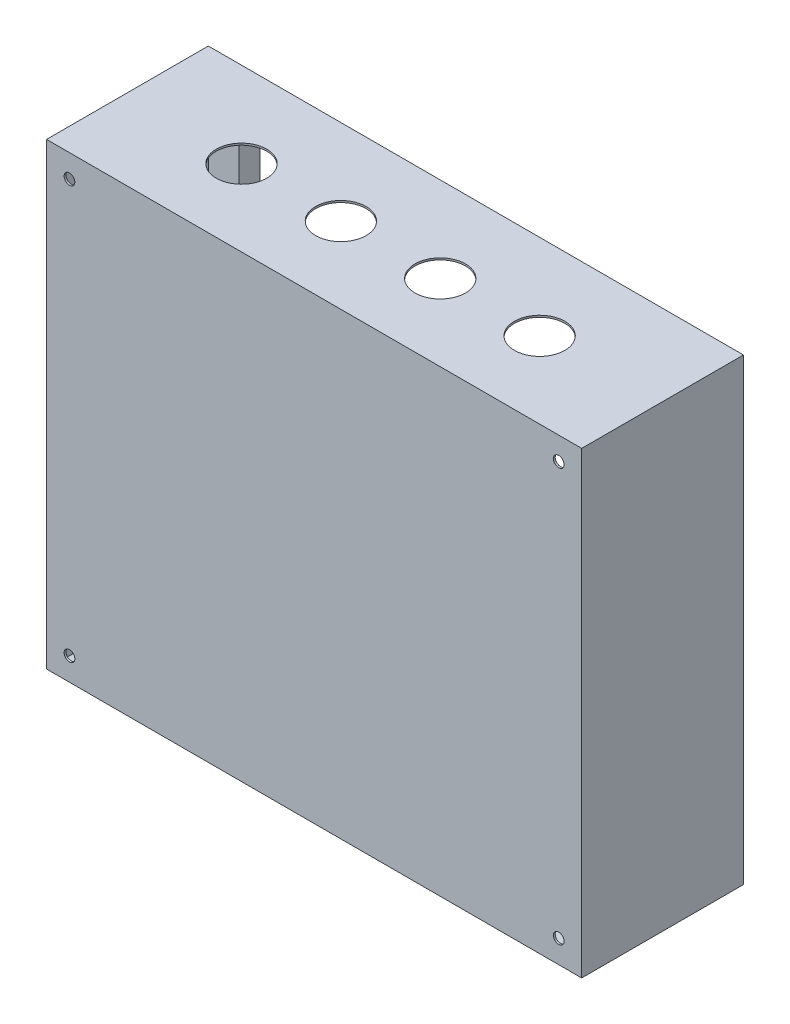
SolidWorks part; units mm, degrees
ref_plane "前视基准面" through (0, 0, 0) normal (0, 0, 1) x (1, 0, 0)
ref_plane "上视基准面" through (0, 0, 0) normal (0, 1, 0) x (1, 0, 0)
ref_plane "右视基准面" through (0, 0, 0) normal (1, 0, 0) x (0, 0, -1)
sketch "草图1" plane through (0, 0, 0) normal (0, 0, 1) x (1, 0, 0)
  line L0 (-175, -150) -> (-175, 150)
  line L1 (-175, -150) -> (175, -150)
  line L2 (-175, 150) -> (175, 150)
  line L3 (175, -150) -> (175, 150)
  line L4 (-175, -150) -> (175, 150) construction
  line L5 (-175, 150) -> (175, -150) construction
  point P1 (0, 0)
  dimension "D1" = 350
  dimension "D2" = 300
extrude "凸台-拉伸1" add sketch "草图1" along normal mid plane 105.8
sketch "草图2" plane through (0, 0, -52.9) normal (0, 0, -1) x (-1, 0, 0)
  line L15 (-155, -130) -> (155, -130)
  line L16 (155, -130) -> (155, 130)
  line L17 (155, 130) -> (-155, 130)
  line L18 (-155, 130) -> (-155, -130)
  line L19 (-155, -130) -> (155, -130)
  line L20 (155, -130) -> (155, 130)
  line L21 (155, 130) -> (-155, 130)
  line L22 (-155, 130) -> (-155, -130)
  dimension "D1" = 20
extrude "凸台-拉伸2" add sketch "草图2" along normal blind 12
sketch "草图6" plane through (0, 0, -64.9) normal (0, 0, -1) x (-1, 0, 0)
  line L4 (-155, 130) -> (-155, -130)
  line L5 (155, 130) -> (-155, 130)
  line L6 (155, -130) -> (155, 130)
  line L7 (-155, -130) -> (155, -130)
  line L8 (-155, 130) -> (-155, -130)
  line L9 (155, 130) -> (-155, 130)
  line L10 (155, -130) -> (155, 130)
  line L11 (-155, -130) -> (155, -130)
  dimension "D1" = 0
extrude "凸台-拉伸3" add sketch "草图6" along normal blind 4 draft 45 draft outward yes
shell "抽壳1" thickness 1.2
sketch "草图12" plane through (0, 0, 52.9) normal (0, 0, 1) x (1, 0, 0)
  circle A0 centre (-160, 135) radius 3.5
  circle A1 centre (160, 135) radius 3.5
  circle A2 centre (160, -135) radius 3.5
  circle A3 centre (-160, -135) radius 3.5
  dimension "D2" = 7
extrude "切除-拉伸3" cut sketch "草图12" against normal up to next
sketch "草图13" plane through (0, 150, 0) normal (0, 1, 0) x (1, 0, 0)
  circle A0 centre (-32.5, -2.9) radius 16.5
  circle A1 centre (32.5, -2.9) radius 16.5
  circle A2 centre (97.5, -2.9) radius 16.5
  circle A3 centre (-97.5, -2.9) radius 16.5
  dimension "D4" = 33
  dimension "D5" = 3
  dimension "D6" = 2
extrude "切除-拉伸4" cut sketch "草图13" against normal up to next
sketch "草图14" plane through (0, 0, -52.9) normal (0, 0, -1) x (-1, 0, 0)
  line L0 (-155, 130) -> (-175, 150)
  line L1 (155, 130) -> (175, 150)
  line L2 (155, -130) -> (175, -150)
  line L3 (-155, -130) -> (-175, -150)
